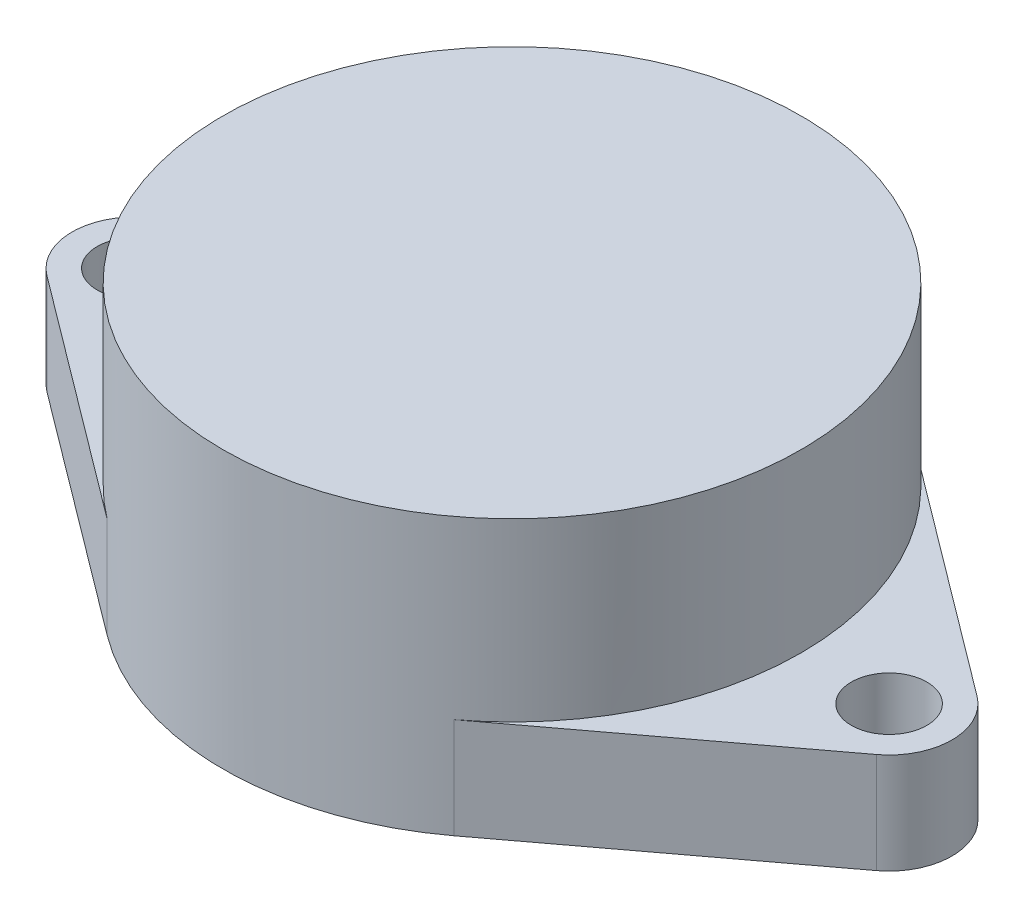
SolidWorks part; units mm, degrees
ref_plane "Alzado" through (0, 0, 0) normal (0, 0, 1) x (1, 0, 0)
ref_plane "Planta" through (0, 0, 0) normal (0, 1, 0) x (1, 0, 0)
ref_plane "Vista lateral" through (0, 0, 0) normal (1, 0, 0) x (0, 0, -1)
sketch "Croquis1" plane through (0, 0, 0) normal (0, 1, 0) x (1, 0, 0)
  line L0 (16.5, 2) -> (6.9, 9.2)
  line L1 (16.5, -2) -> (6.9, -9.2)
  line L2 (-16.5, 2) -> (-6.9, 9.2)
  line L3 (-16.5, -2) -> (-6.9, -9.2)
  line L4 (-17.5, 0) -> (17.5, 0) construction
  arc A0 (-6.9, -9.2) -> (6.9, -9.2) centre (0, 0) ccw
  arc A1 (16.5, -2) -> (16.5, 2) centre (15, 0) ccw
  arc A2 (-16.5, 2) -> (-16.5, -2) centre (-15, 0) ccw
  arc A3 (6.9, 9.2) -> (-6.9, 9.2) centre (0, 0) ccw
  circle A4 centre (-15, 0) radius 1.5
  circle A5 centre (15, 0) radius 1.5
  point P15 (0, 0)
  dimension "D1" = 23
  dimension "D4" = 3
  dimension "D2" = 35
  dimension "D3" = 30
extrude "Saliente-Extruir1" add sketch "Croquis1" along normal blind 4
sketch "Croquis2" plane through (0, 4, 0) normal (0, 1, 0) x (1, 0, 0)
  circle A0 centre (0, 0) radius 11.5
  arc A1 (-6.9, -9.2) -> (6.9, -9.2) centre (0, 0) ccw construction
extrude "Saliente-Extruir2" add sketch "Croquis2" along normal blind 7
